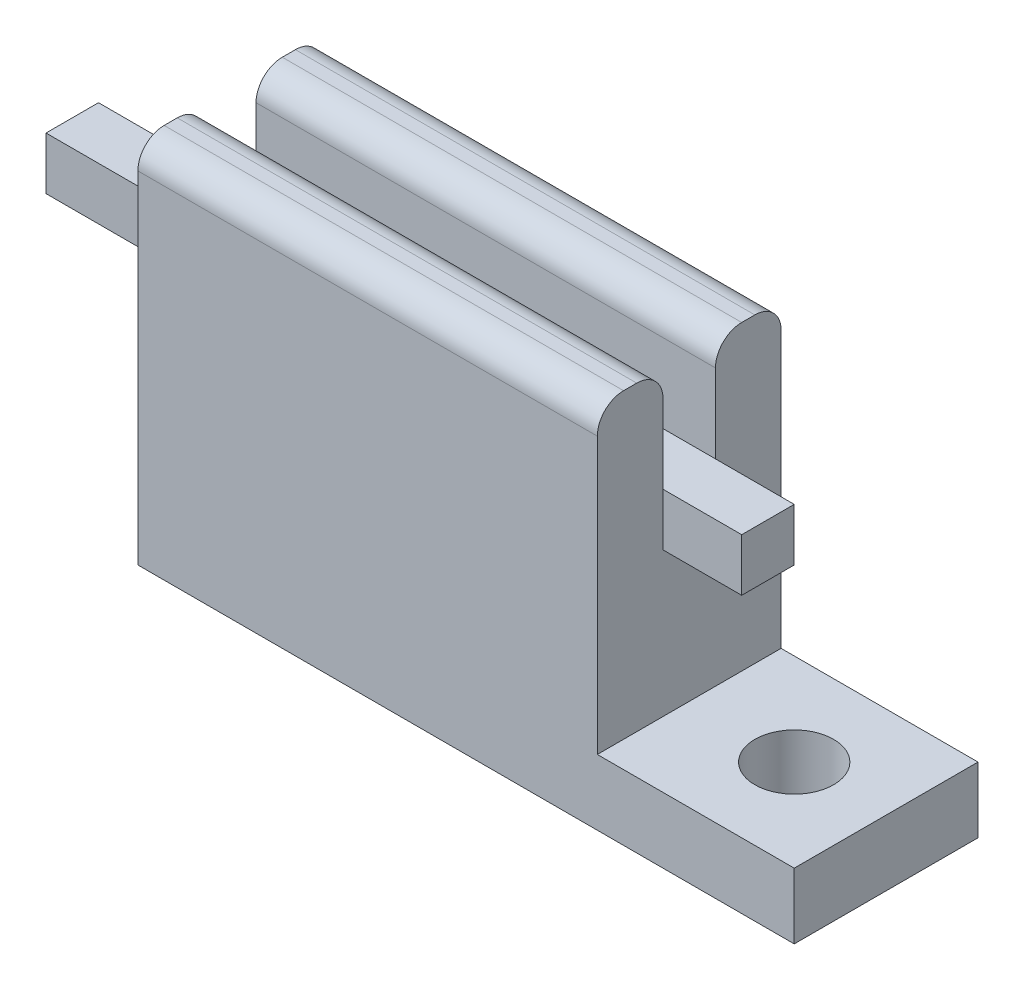
SolidWorks part; units mm, degrees
ref_plane "Спереди" through (0, 0, 0) normal (0, 0, 1) x (1, 0, 0)
ref_plane "Сверху" through (0, 0, 0) normal (0, 1, 0) x (1, 0, 0)
ref_plane "Справа" through (0, 0, 0) normal (1, 0, 0) x (0, 0, -1)
sketch "Эскиз1" plane through (0, 0, 0) normal (0, 1, 0) x (1, 0, 0)
  line L0 (-43, 7) -> (-43, -7)
  line L1 (-43, -7) -> (7, -7)
  line L5 (7, -7) -> (7, 7)
  line L6 (7, 7) -> (-43, 7)
  circle A0 centre (0, 0) radius 3
extrude "Бобышка-Вытянуть1" add sketch "Эскиз1" along normal blind 5
ref_plane "Плоскость1" through (0, 5, 0) normal (0, 1, 0) x (1, 0, 0)
sketch "Эскиз2" plane through (0, 5, 0) normal (0, 1, 0) x (1, 0, 0)
  line L0 (-43, -7) -> (-8, -7)
  line L1 (-43, -7) -> (7, -7) construction
  line L2 (-8, -7) -> (-8, 7)
  line L3 (7, 7) -> (-43, 7) construction
  line L4 (-8, 7) -> (-43, 7)
  line L5 (-43, 7) -> (-43, -7)
extrude "Бобышка-Вытянуть2" add sketch "Эскиз2" along normal blind 15
ref_plane "Плоскость2" through (0, 20, 0) normal (0, 1, 0) x (1, 0, 0)
sketch "Эскиз3" plane through (0, 20, 0) normal (0, 1, 0) x (1, 0, 0)
  line L0 (-43, -7) -> (-43, -2)
  line L1 (-43, 7) -> (-43, -7) construction
  line L2 (-43, 7) -> (-43, 2)
  line L3 (-43, 2) -> (-8, 2)
  line L4 (-8, -7) -> (-8, 7) construction
  line L5 (-8, 2) -> (-8, 7)
  line L6 (-8, -7) -> (-8, 7) construction
  line L7 (-43, 7) -> (-8, 7)
  line L8 (-43, -2) -> (-8, -2)
  line L9 (-8, -2) -> (-8, -7)
  line L10 (-8, -7) -> (-43, -7)
extrude "Бобышка-Вытянуть3" add sketch "Эскиз3" along normal blind 8
sketch "Эскиз4" plane through (0, 20, 0) normal (0, 1, 0) x (1, 0, 0)
  line L0 (-43, 2) -> (-55, 2)
  line L1 (-55, 2) -> (-55, -2)
  line L2 (-55, -2) -> (-43, -2)
  line L3 (-43, -2) -> (-43, 2)
  line L4 (-8, 2) -> (-2, 2)
  line L5 (-2, 2) -> (-2, -2)
  line L6 (-2, -2) -> (-8, -2)
  line L7 (-8, -2) -> (-8, 2)
extrude "Бобышка-Вытянуть4" add sketch "Эскиз4" against normal blind 4
fillet "Скругление1" radius 2 4 edges at (-25.5, 28, 7) (-25.5, 28, -2) (-25.5, 28, -7) (-25.5, 28, 2)
